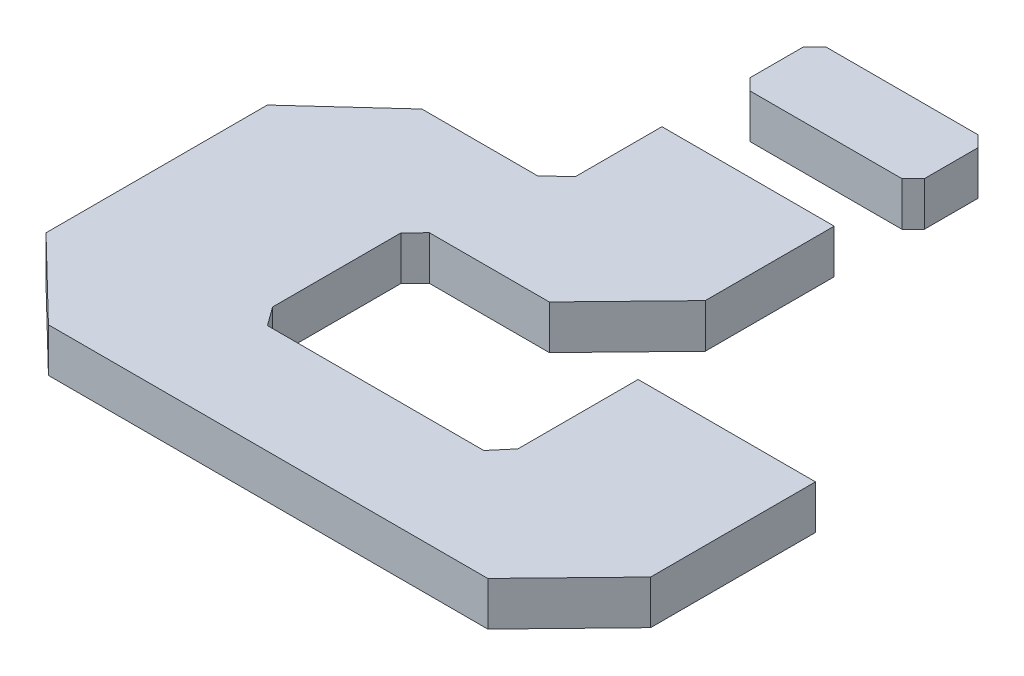
SolidWorks part; units mm, degrees
ref_plane "前视基准面" through (0, 0, 0) normal (0, 0, 1) x (1, 0, 0)
ref_plane "上视基准面" through (0, 0, 0) normal (0, 1, 0) x (1, 0, 0)
ref_plane "右视基准面" through (0, 0, 0) normal (1, 0, 0) x (0, 0, -1)
sketch "草图1" plane through (0, 0, 0) normal (0, 1, 0) x (1, 0, 0)
  line L0 (-41.1672, 152.4617) -> (-357.8339, 152.4617) construction
  line L1 (26.0376, -7.5478) -> (26.0376, -19.1477) construction
  line L2 (26.0376, -19.1477) -> (20.3237, -25.0389) construction
  line L3 (20.3237, -25.0389) -> (-10.0502, -25.0389) construction
  line L4 (-10.0502, -25.0389) -> (-15.8188, -19.4441) construction
  line L5 (-15.8188, -19.4441) -> (-15.8188, -3.9647) construction
  line L6 (-15.8188, -3.9647) -> (-10.0502, 1.3068) construction
  line L7 (-10.0502, 1.3068) -> (-2.1493, 1.3068) construction
  line L8 (-2.1493, 1.3068) -> (-1.0443, 2.3165) construction
  line L9 (-1.0443, 2.3165) -> (-1.0443, 8.4682) construction
  line L10 (-1.0443, 8.4682) -> (11.5357, 8.4682) construction
  line L11 (11.5357, 8.4682) -> (11.5357, -0.9115) construction
  line L12 (11.5357, -0.9115) -> (6.0553, -6.5621) construction
  line L13 (6.0553, -6.5621) -> (-2.1493, -6.5621) construction
  line L14 (-2.1493, -6.5621) -> (-2.8791, -7.3146) construction
  line L15 (-2.8791, -7.3146) -> (-2.8791, -15.791) construction
  line L16 (-2.8791, -15.791) -> (-2.1493, -16.7976) construction
  line L17 (-2.1493, -16.7976) -> (12.2567, -16.7976) construction
  line L18 (12.2567, -16.7976) -> (13.1105, -15.791) construction
  line L19 (13.1105, -15.791) -> (13.1105, -7.3146) construction
  line L20 (13.1105, -7.3146) -> (26.0376, -7.3146) construction
  line L21 (26.0376, -7.3146) -> (26.0376, -7.5478) construction
  line L22 (10.8051, 12.7965) -> (11.8051, 13.7965) construction
  line L23 (10.8051, 12.7965) -> (0.0687, 12.7965) construction
  line L24 (11.8051, 13.7965) -> (11.8051, 17.7965) construction
  line L25 (10.8051, 18.7965) -> (0.0687, 18.7965) construction
  line L26 (-0.9313, 13.7965) -> (-0.9313, 17.7965) construction
  line L27 (11.8051, 12.7965) -> (-0.9313, 18.7965) construction
  line L28 (11.8051, 18.7965) -> (-0.9313, 12.7965) construction
  line L29 (0.0687, 12.7965) -> (-0.9313, 13.7965) construction
  line L30 (-0.9313, 17.7965) -> (0.0687, 18.7965) construction
  line L31 (11.8051, 17.7965) -> (10.8051, 18.7965) construction
  line L32 (-28.9447, -3.2621) -> (41.0553, -3.2621) construction
  line L33 (6.0553, 22.7423) -> (6.0553, -32.2577) construction
  line L34 (25.6376, -18.9856) -> (25.6376, -7.7146)
  line L35 (25.6376, -18.9856) -> (20.1544, -24.6389)
  line L36 (20.1544, -24.6389) -> (-9.8881, -24.6389)
  line L37 (-9.8881, -24.6389) -> (-15.4188, -19.2748)
  line L38 (-15.4188, -19.2748) -> (-15.4188, -4.141)
  line L39 (-15.4188, -4.141) -> (-9.895, 0.9068)
  line L40 (-9.895, 0.9068) -> (-1.994, 0.9068)
  line L41 (-1.994, 0.9068) -> (-0.6443, 2.1401)
  line L42 (-0.6443, 2.1401) -> (-0.6443, 8.0682)
  line L43 (-0.6443, 8.0682) -> (11.1357, 8.0682)
  line L44 (11.1357, 8.0682) -> (11.1357, -0.7494)
  line L45 (11.1357, -0.7494) -> (5.886, -6.1621)
  line L46 (5.886, -6.1621) -> (-2.3185, -6.1621)
  line L47 (-2.3185, -6.1621) -> (-3.2791, -7.1525)
  line L48 (-3.2791, -7.1525) -> (-3.2791, -15.9207)
  line L49 (-3.2791, -15.9207) -> (-2.3533, -17.1976)
  line L50 (-2.3533, -17.1976) -> (12.4419, -17.1976)
  line L51 (12.4419, -17.1976) -> (13.5105, -15.9378)
  line L52 (13.5105, -15.9378) -> (13.5105, -7.7146)
  line L53 (25.6376, -7.7146) -> (13.5105, -7.7146)
  line L55 (10.6394, 13.1965) -> (11.4051, 13.9622)
  line L56 (11.4051, 13.9622) -> (11.4051, 17.6309)
  line L57 (11.4051, 17.6309) -> (10.6394, 18.3965)
  line L58 (10.6394, 18.3965) -> (0.2344, 18.3965)
  line L59 (-0.5313, 17.6309) -> (0.2344, 18.3965)
  line L60 (-0.5313, 13.9622) -> (-0.5313, 17.6309)
  line L61 (0.2344, 13.1965) -> (-0.5313, 13.9622)
  line L62 (10.6394, 13.1965) -> (0.2344, 13.1965)
  line L63 (11.6346, 12.4347) -> (-1.1018, 18.4347) construction
  line L64 (11.9755, 18.4347) -> (-0.7609, 12.4347) construction
  line L65 (-28.9447, -2.8621) -> (41.0553, -2.8621) construction
  line L66 (6.4553, 22.7423) -> (6.4553, -32.2577) construction
  line L67 (25.6376, -7.7146) -> (25.6376, -18.9856) construction
  line L68 (13.5105, -7.7146) -> (25.6376, -7.7146) construction
  line L69 (25.6376, -7.7146) -> (25.6376, -7.7146) construction
  point P20 (5.4369, 15.7965)
  dimension "D1" = 0.4
extrude "凸台-拉伸1" add sketch "草图1" along normal blind 3
